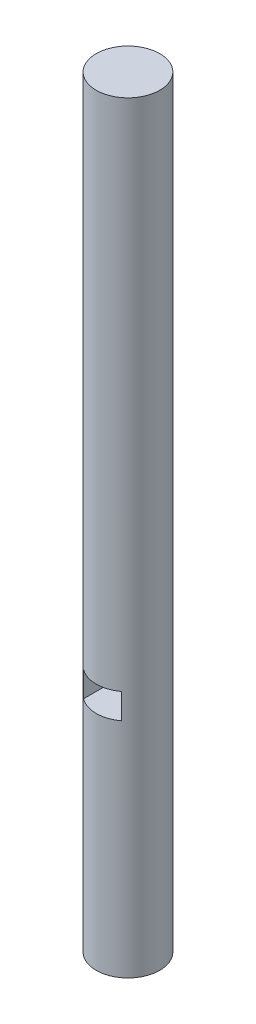
SolidWorks part; units mm, degrees
ref_plane "Front Plane" through (0, 0, 0) normal (0, 0, 1) x (1, 0, 0)
ref_plane "Top Plane" through (0, 0, 0) normal (0, 1, 0) x (1, 0, 0)
ref_plane "Right Plane" through (0, 0, 0) normal (1, 0, 0) x (0, 0, -1)
sketch "Sketch1" plane through (0, 0, 0) normal (0, 1, 0) x (1, 0, 0)
  circle A0 centre (0, 0) radius 5
extrude "Boss-Extrude1" add sketch "Sketch1" along normal blind 120
sketch "Sketch2" plane through (0, 0, 0) normal (0, 0, 1) x (1, 0, 0)
  line L0 (0, 0) -> (0, 35.0323)
  line L7 (-3, 39.0323) -> (3, 39.0323)
  line L8 (-3, 39.0323) -> (-3, 35.0323)
  line L9 (-3, 35.0323) -> (3, 35.0323)
  line L10 (3, 39.0323) -> (3, 35.0323)
  point P6 (0, 35.0323)
extrude "Cut-Extrude1" cut sketch "Sketch2" against normal mid plane 120 contours L7 L10 L9 L8
